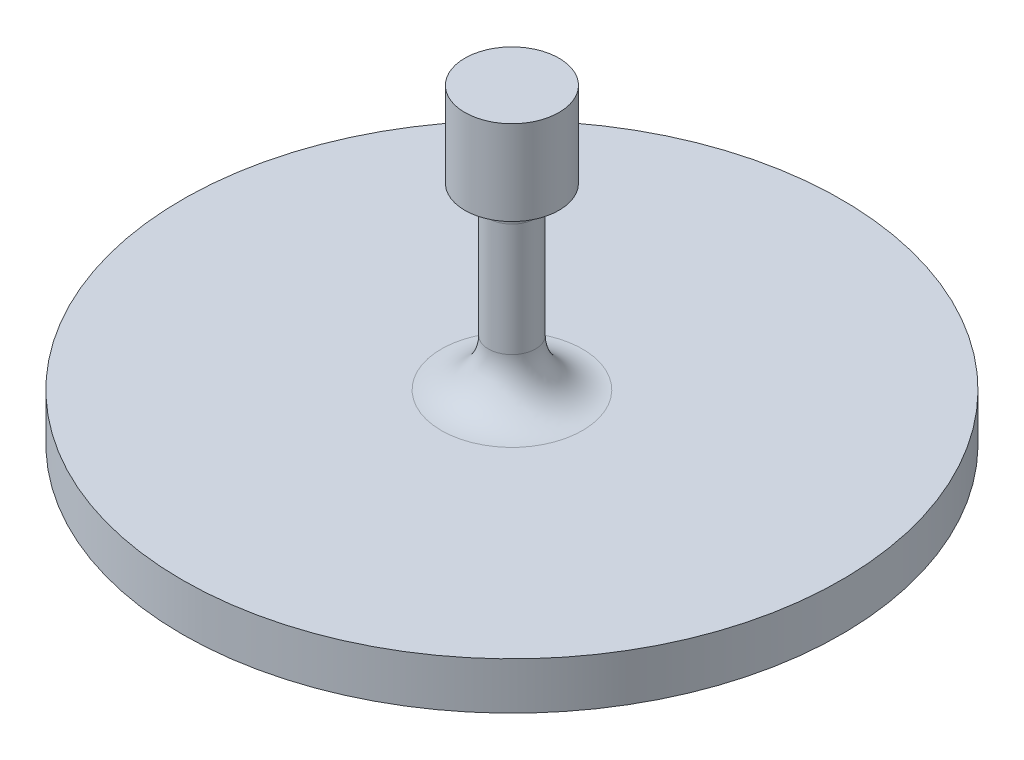
SolidWorks part; units mm, degrees
ref_plane "前视基准面" through (0, 0, 0) normal (0, 0, 1) x (1, 0, 0)
ref_plane "上视基准面" through (0, 0, 0) normal (0, 1, 0) x (1, 0, 0)
ref_plane "右视基准面" through (0, 0, 0) normal (1, 0, 0) x (0, 0, -1)
other "Configuration Table"
sketch "草图1" plane through (0, 0, 0) normal (0, 1, 0) x (1, 0, 0)
  circle A0 centre (0, 0) radius 35
  dimension "D1" = 70
extrude "凸台-拉伸1" add sketch "草图1" along normal blind 5
sketch "草图2" plane through (0, 5, 0) normal (0, 1, 0) x (1, 0, 0)
  circle A0 centre (0, 0) radius 2.5
  dimension "D1" = 5
extrude "凸台-拉伸2" add sketch "草图2" along normal blind 19
sketch "草图3" plane through (0, 24, 0) normal (0, 1, 0) x (1, 0, 0)
  circle A0 centre (0, 0) radius 5
  dimension "D1" = 10
extrude "凸台-拉伸3" add sketch "草图3" along normal blind 9
fillet "圆角1" radius 5 1 edges at (0, 5, 2.5)
fillet "圆角2" radius 2 1 edges at (0, 24, 2.5)
